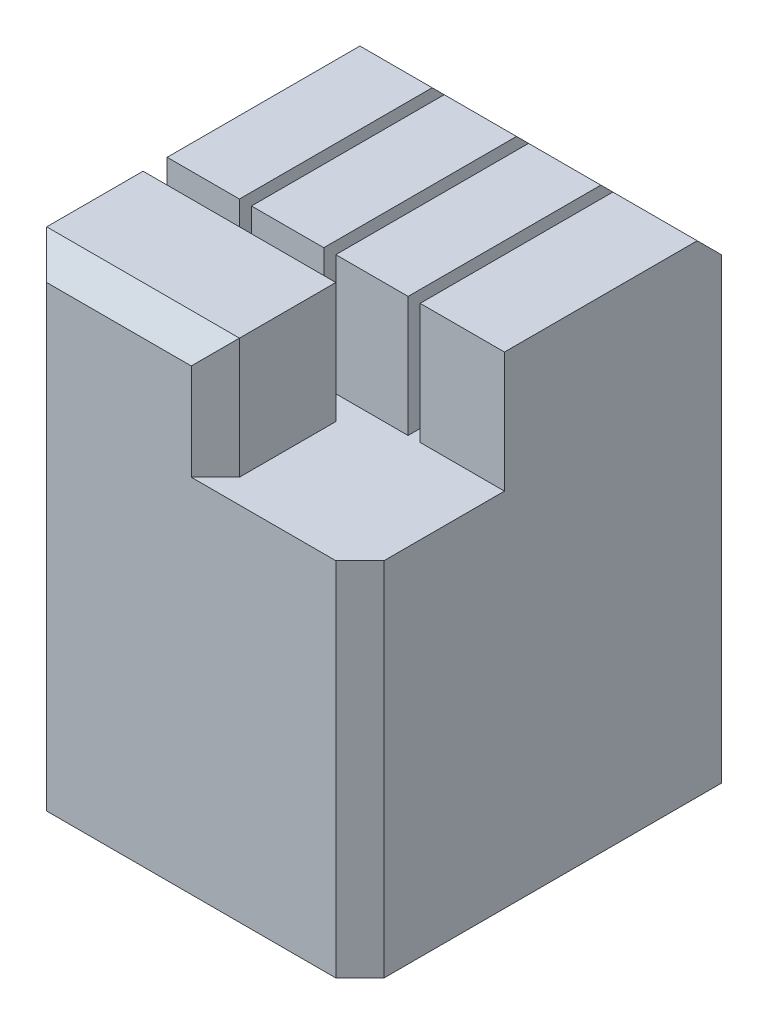
SolidWorks part; units mm, degrees
ref_plane "Front Plane" through (0, 0, 0) normal (0, 0, 1) x (1, 0, 0)
ref_plane "Top Plane" through (0, 0, 0) normal (0, 1, 0) x (1, 0, 0)
ref_plane "Right Plane" through (0, 0, 0) normal (1, 0, 0) x (0, 0, -1)
sketch "Sketch1" plane through (0, 0, 0) normal (0, 1, 0) x (1, 0, 0)
  line L1 (0, 0) -> (14, 0)
  line L2 (0, 0) -> (0, 16)
  line L3 (0, 16) -> (14, 16)
  line L4 (14, 0) -> (14, 16)
  dimension "D1" = 14
  dimension "D2" = 16
extrude "Boss-Extrude1" add sketch "Sketch1" against normal blind 20
sketch "Sketch2" plane through (0, 0, 0) normal (0, 1, 0) x (1, 0, 0)
  line L0 (0, 16) -> (0, 0) construction
  line L1 (0, 6) -> (3, 6)
  line L2 (0, 6) -> (0, 5)
  line L3 (0, 0) -> (8, 0)
  line L5 (0, 0) -> (14, 0) construction
  line L6 (14, 16) -> (0, 16) construction
  line L7 (3, 16) -> (3.5, 16)
  line L8 (3, 16) -> (3, 6)
  line L10 (3.5, 16) -> (3.5, 6)
  line L12 (6.5, 16) -> (7, 16)
  line L13 (6.5, 16) -> (6.5, 6)
  line L15 (7, 16) -> (7, 6)
  line L16 (10, 16) -> (10.5, 16)
  line L17 (10, 16) -> (10, 6)
  line L19 (10.5, 16) -> (10.5, 6)
  line L20 (0, 6) -> (3, 6)
  line L21 (0, 6) -> (0, 5)
  line L24 (10.5, 6) -> (14, 6)
  line L25 (7, 6) -> (10, 6)
  line L26 (3.5, 6) -> (6.5, 6)
  line L27 (3.5, 6) -> (6.5, 6)
  line L28 (0, 5) -> (0, 0)
  line L29 (0, 5) -> (8, 5)
  line L30 (0, 5) -> (0, 0)
  line L31 (0, 0) -> (8, 0)
  line L32 (8, 5) -> (8, 0)
  line L33 (8, 0) -> (14, 0)
  line L34 (14, 0) -> (14, 6)
  line M19 (0, 16) -> (0, 0)
  line M20 (0, 0) -> (14, 0)
  line M21 (14, 0) -> (14, 16)
  line M22 (14, 16) -> (0, 16)
  dimension "D1" = 0.5
  dimension "D2" = 0.5
  dimension "D3" = 0.5
  dimension "D4" = 3.5
  dimension "D5" = 3
  dimension "D6" = 3
  dimension "D7" = 5
  dimension "D8" = 10
  dimension "D9" = 8
extrude "Cut-Extrude1" cut sketch "Sketch2" against normal blind 5 contours L29 L32 L24 L19 L17 L25 L15 L13 L26 L10 L8 L1 M20 M21 M22 M19
chamfer "Chamfer1" distance 2 angle 45 4 edges at (1.5, 0, -16) (5, 0, -16) (8.5, 0, -16) (12.25, 0, -16)
chamfer "Chamfer2" distance 1 angle 45 6 edges at (4, 0, 0) (14, -12.5, 0) (0, -11, -16) (14, -11, -16) (8, -2.5, 0) (0, -10, 0)
sketch "Sketch4" plane through (0, -20, 0) normal (0, -1, 0) x (1, 0, 0)
  line L0 (1, 0) -> (13, 0) construction
  line L1 (0, -15) -> (0, -1) construction
  circle A0 centre (7, -8) radius 5
  dimension "D1" = 10
  dimension "D2" = 8
  dimension "D3" = 7
extrude "Cut-Extrude2" cut sketch "Sketch4" against normal blind 12
